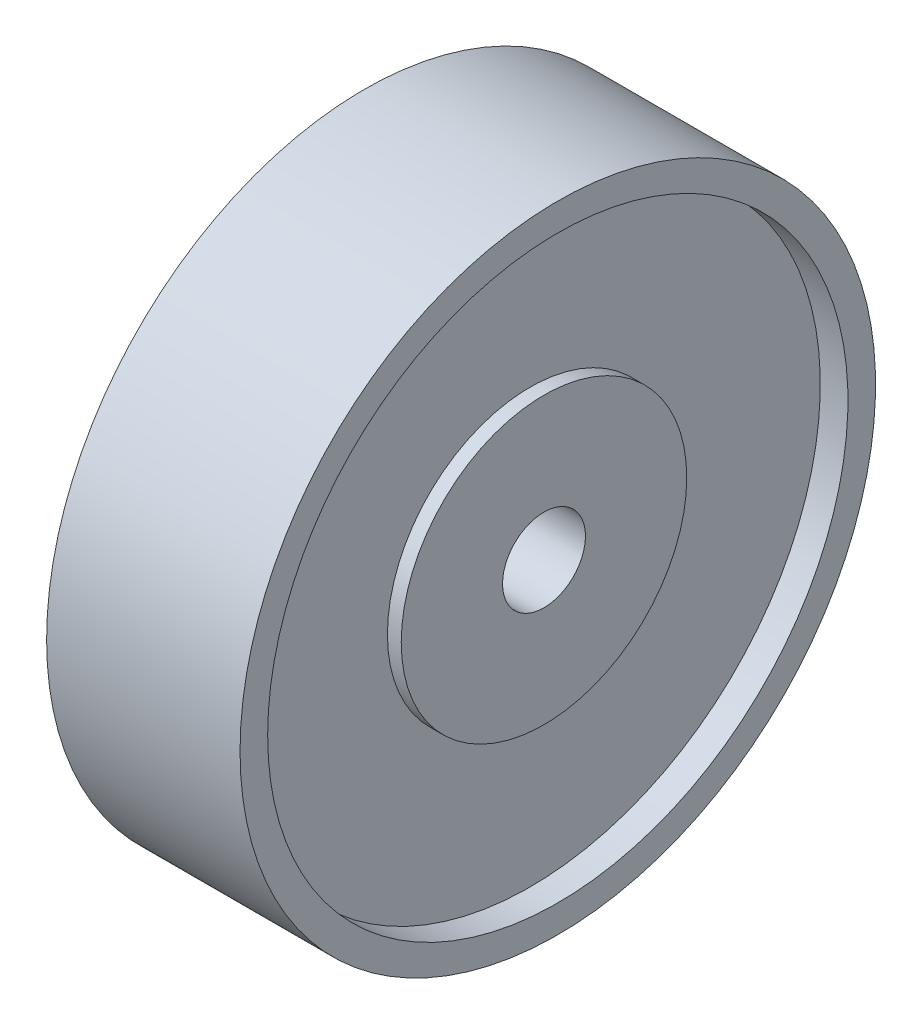
SolidWorks part; units mm, degrees
ref_plane "Front Plane" through (0, 0, 0) normal (0, 0, 1) x (1, 0, 0)
ref_plane "Top Plane" through (0, 0, 0) normal (0, 1, 0) x (1, 0, 0)
ref_plane "Right Plane" through (0, 0, 0) normal (1, 0, 0) x (0, 0, -1)
sketch "Sketch3" plane through (0, 0, 0) normal (0, 0, 1) x (1, 0, 0)
  line L0 (0, 0) -> (0, 93.3201) construction
  line L1 (0, 0) -> (122.7839, 0) construction
  line L2 (0, 15) -> (0, 115)
  line L3 (-35, 115) -> (35, 115)
  line L4 (35, 115) -> (35, 105)
  line L5 (35, 105) -> (25, 105)
  line L7 (25, 15) -> (-25, 15)
  line L8 (-35, 105) -> (-25, 105)
  line L10 (-35, 115) -> (-35, 105)
  line L11 (25, 105) -> (25, 51.6658)
  line L12 (25, 51.6658) -> (30, 51.6658)
  line L13 (30, 51.6658) -> (30, 15)
  line L14 (30, 15) -> (25, 15)
  line L15 (-30, 51.6658) -> (-30, 15)
  line L16 (-25, 51.6658) -> (-30, 51.6658)
  line L17 (-25, 105) -> (-25, 51.6658)
  line L18 (-25, 15) -> (-30, 15)
  dimension "D1" = 35
  dimension "D2" = 15
  dimension "D3" = 5
  dimension "D4" = 10
  dimension "D5" = 10
revolve "Revolve1" add sketch "Sketch3" angle 360 about L1
